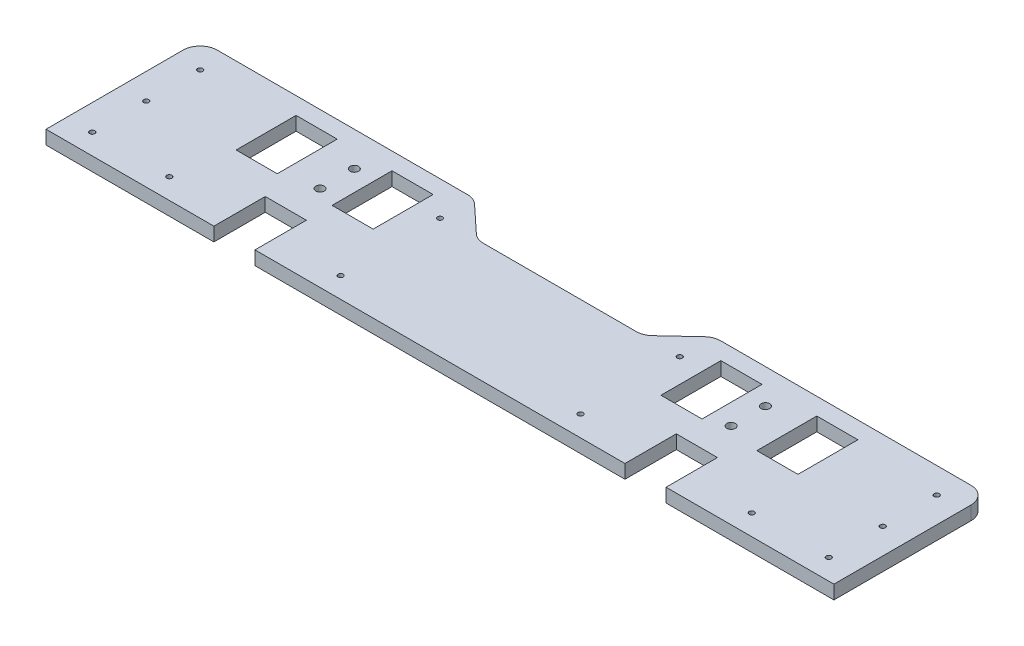
SolidWorks part; units mm, degrees
ref_plane "前视基准面" through (0, 0, 0) normal (0, 0, 1) x (1, 0, 0)
ref_plane "上视基准面" through (0, 0, 0) normal (0, 1, 0) x (1, 0, 0)
ref_plane "右视基准面" through (0, 0, 0) normal (1, 0, 0) x (0, 0, -1)
sketch "草图1" plane through (0, 0, 0) normal (0, 1, 0) x (1, 0, 0)
  line L1 (230, -45) -> (-230, -45)
  line L2 (230, -45) -> (230, 45)
  line L3 (230, 45) -> (-230, 45)
  line L4 (-230, -45) -> (-230, 45)
  line L5 (230, -45) -> (-230, 45) construction
  line L6 (230, 45) -> (-230, -45) construction
  point P0 (0, 0)
  dimension "D1" = 460
  dimension "D2" = 90
extrude "凸台-拉伸1" add sketch "草图1" along normal blind 8 contours L3 L4 L1 L2
sketch "草图2" plane through (0, 8, 0) normal (0, 1, 0) x (1, 0, 0)
  line L0 (0, 55) -> (0, -55) construction
  line L1 (230, 45) -> (-230, 45) construction
  line L2 (230, -45) -> (-230, -45) construction
  line L3 (-120, 45) -> (-120, -45) construction
  line L4 (120, 45) -> (120, -45) construction
  line L5 (-230, -45) -> (-230, 45) construction
  line L6 (230, -45) -> (230, 45) construction
  line L8 (140, 35) -> (164, 35)
  line L9 (140, 35) -> (140, 0)
  line L10 (140, 0) -> (164, 0)
  line L11 (164, 35) -> (164, 0)
  line L12 (140, 35) -> (164, 0) construction
  line L13 (140, 0) -> (164, 35) construction
  line L14 (84, 35) -> (108, 35)
  line L15 (84, 35) -> (84, 0)
  line L16 (84, 0) -> (108, 0)
  line L17 (108, 35) -> (108, 0)
  line L18 (84, 35) -> (108, 0) construction
  line L19 (84, 0) -> (108, 35) construction
  point P14 (152, 17.5)
  point P19 (96, 17.5)
  dimension "D1" = 110
  dimension "D2" = 110
  dimension "D3" = 24
  dimension "D4" = 35
  dimension "D5" = 10
  dimension "D6" = 12
  dimension "D7" = 20
sketch "草图3" plane through (0, 8, 0) normal (0, 1, 0) x (1, 0, 0)
  line L0 (70, 45) -> (48.5526, 25)
  line L1 (230, 45) -> (-230, 45) construction
  line L2 (48.5526, 25) -> (-48.5526, 25)
  line L3 (-48.5526, 25) -> (-70, 45)
  line L4 (230, -45) -> (230, 45) construction
  line L5 (-70, 45) -> (70, 45)
  line L8 (108, -45) -> (108, -15)
  line L9 (108, -15) -> (132, -15)
  line L10 (132, -45) -> (132, -15)
  line L11 (108, -45) -> (132, -15) construction
  line L12 (108, -15) -> (132, -45) construction
  line L14 (108, -45) -> (132, -45)
  line M4 (-230, -45) -> (230, -45)
  dimension "D1" = 20
  dimension "D2" = 43
  dimension "D3" = 43
  dimension "D4" = 160
  dimension "D5" = 160
  dimension "D6" = 60
  dimension "D7" = 24
  dimension "D8" = 98
  dimension "D9" = 30
extrude "切除-拉伸2" cut sketch "草图3" against normal through all contours L10 L9 L8 M4 | L5 L0 L2 L3
extrude "切除-拉伸3" cut sketch "草图2" against normal through all contours L11 L8 L9 L10 | L17 L16 L15 L14
mirror "镜向1" about plane through (0, 0, 0) normal (1, 0, 0) of "切除-拉伸2", "切除-拉伸3"
fillet "圆角1" radius 10 6 edges at (-230, 4, -45) (48.5526, 4, -25) (-70, 4, -45) (-48.5526, 4, -25) (70, 4, -45) (230, 4, -45)
sketch "草图19" plane through (0, 8, 0) normal (0, 1, 0) x (1, 0, 0)
  line L0 (-120, -15) -> (-120, 45) construction
  line L1 (-108, -15) -> (-132, -15) construction
  line L2 (-73.9391, 45) -> (-220, 45) construction
  line L3 (108, -15) -> (132, -15) construction
  line L4 (120, -15) -> (120, 45) construction
  line L5 (220, 45) -> (73.9391, 45) construction
  circle A0 centre (-120, 5) radius 2.5
  circle A1 centre (-120, 25) radius 2.5
  point P16 (0, 0)
  dimension "D1" = 20
  dimension "D2" = 20
extrude "切除-拉伸4" cut sketch "草图19" against normal through all contours A0 | A1
mirror "镜向2" about plane through (0, 0, 0) normal (1, 0, 0) of "切除-拉伸4"
sketch "草图20" plane through (0, 8, 0) normal (0, 1, 0) x (1, 0, 0)
  line L1 (-132, -45) -> (-230, -45) construction
  line L2 (-73.9391, 45) -> (-220, 45) construction
  line L3 (-230, -45) -> (-230, 35) construction
  circle A0 centre (-215, 30) radius 1.5
  circle A1 centre (-215, -1.5) radius 1.5
  circle A2 centre (-215, -33) radius 1.5
  circle A3 centre (-70, 25) radius 1.5
  circle A4 centre (-70, -33) radius 1.5
  circle A5 centre (-170, -33) radius 1.5
  point P4 (0, 0)
  point P5 (0, 0)
  dimension "D1" = 45
  dimension "D7" = 20
  dimension "D2" = 12
  dimension "D3" = 15
  dimension "D4" = 15
  dimension "D5" = 31.5
  dimension "D6" = 160
extrude "切除-拉伸5" cut sketch "草图20" against normal through all
mirror "镜向3" about plane through (0, 0, 0) normal (1, 0, 0) of "切除-拉伸5"
